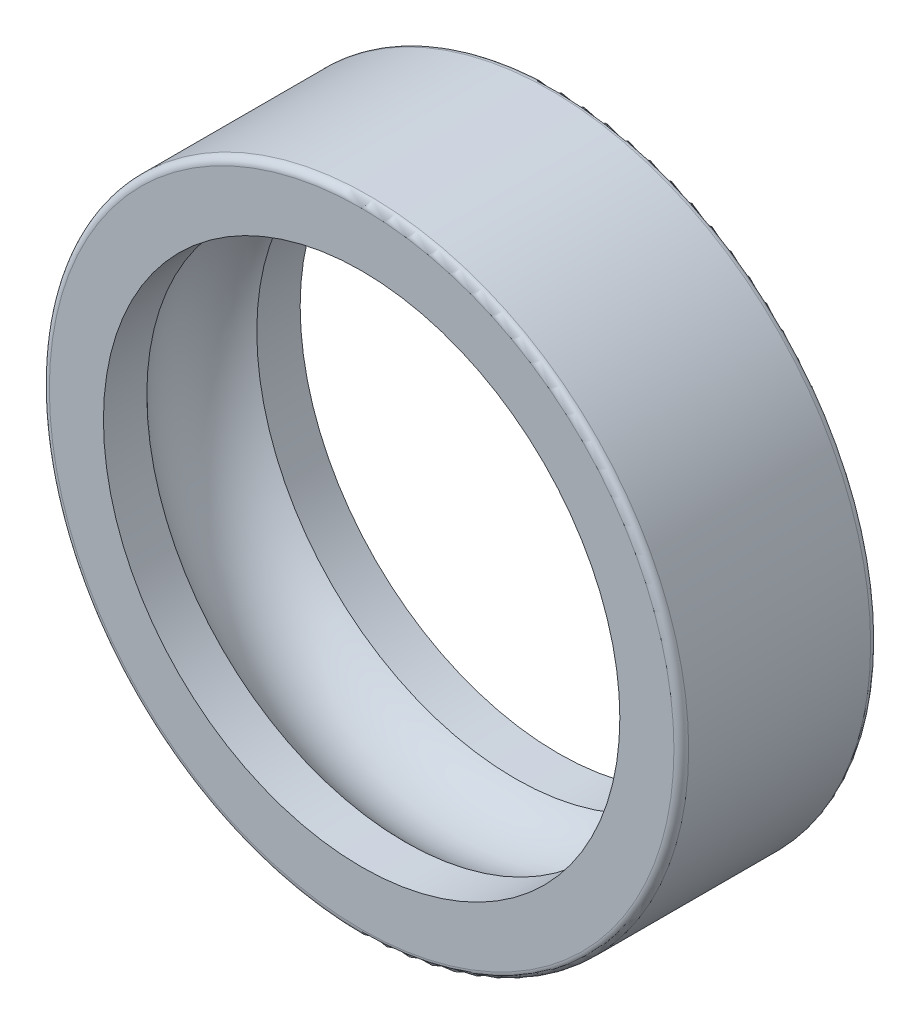
SolidWorks part; units mm, degrees
material "Plain Carbon Steel"
ref_plane "Front Plane" through (0, 0, 0) normal (0, 0, 1) x (1, 0, 0)
ref_plane "Top Plane" through (0, 0, 0) normal (0, 1, 0) x (1, 0, 0)
ref_plane "Right Plane" through (0, 0, 0) normal (1, 0, 0) x (0, 0, -1)
sketch "Sketch1" plane through (0, 0, 0) normal (1, 0, 0) x (0, 0, -1)
  line L0 (-8.5161, 0) -> (9.1613, 0) construction
  line L1 (0, 11.75) -> (0, 0) construction
  line L2 (-3.7, 13) -> (3.7, 13)
  line L3 (-4, 12.7) -> (-4, 10.5)
  line L4 (-4, 10.5) -> (-2.2361, 10.5)
  line L5 (4, 12.7) -> (4, 10.5)
  line L6 (-4, 13) -> (4, 10.5) construction
  line L7 (-4, 10.5) -> (4, 13) construction
  line L8 (0, 11.5) -> (-0.8013, 11.5) construction
  line L9 (2.2361, 10.5) -> (4, 10.5)
  arc A0 (2.2361, 10.5) -> (-2.2361, 10.5) centre (0, 8.5) ccw
  arc A1 (-3.7, 13) -> (-4, 12.7) centre (-3.7, 12.7) ccw
  arc A2 (3.7, 13) -> (4, 12.7) centre (3.7, 12.7) cw
  point P3 (0, 11.75)
  dimension "D4" = 3
  dimension "D5" = 1
  dimension "D6" = 0.3
  dimension "D1" = 8
  dimension "D2" = 2.5
  dimension "D3" = 13
revolve "Revolve1" add sketch "Sketch1" angle 360 about L0
